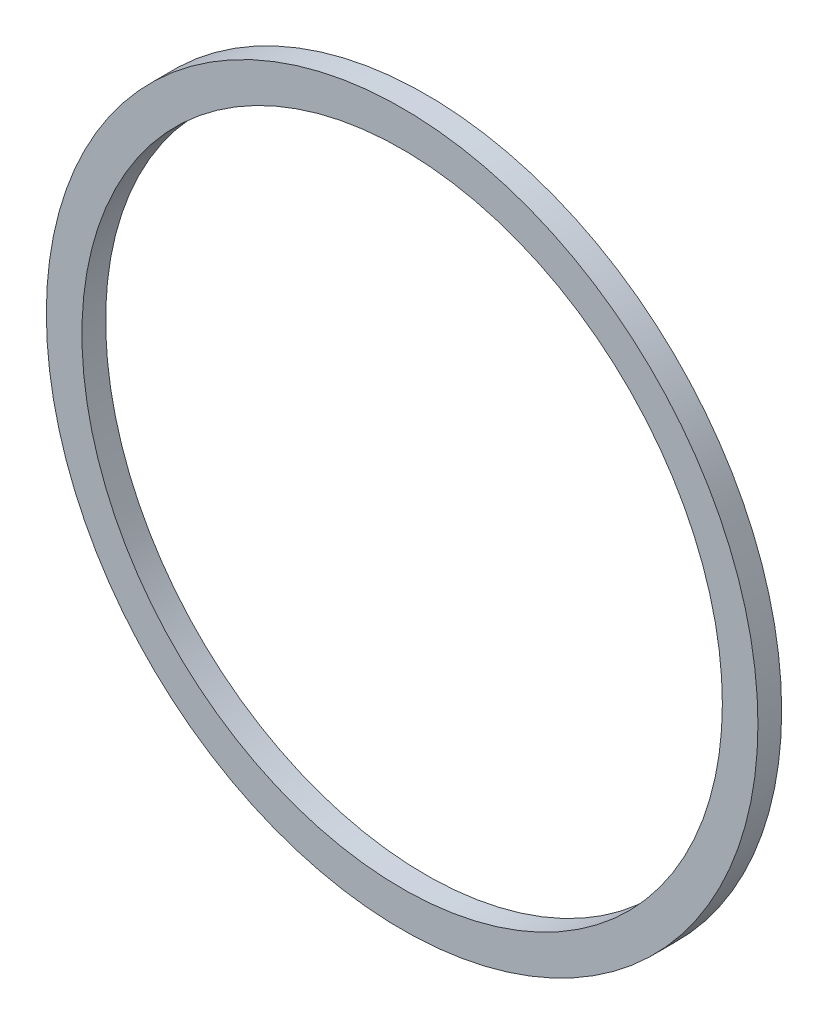
SolidWorks part; units mm, degrees
material "Balsa"
ref_plane "Ebene vorne" through (0, 0, 0) normal (0, 0, 1) x (1, 0, 0)
ref_plane "Ebene oben" through (0, 0, 0) normal (0, 1, 0) x (1, 0, 0)
ref_plane "Ebene rechts" through (0, 0, 0) normal (1, 0, 0) x (0, 0, -1)
sketch "Sketch1" plane through (0, 0, 0) normal (0, 0, 1) x (1, 0, 0)
  circle A0 centre (0, 0) radius 75
  circle A1 centre (0, 0) radius 67.5
  dimension "D1" = 150
  dimension "D2" = 7.5
extrude "Boss-Extrude1" add sketch "Sketch1" along normal blind 5
